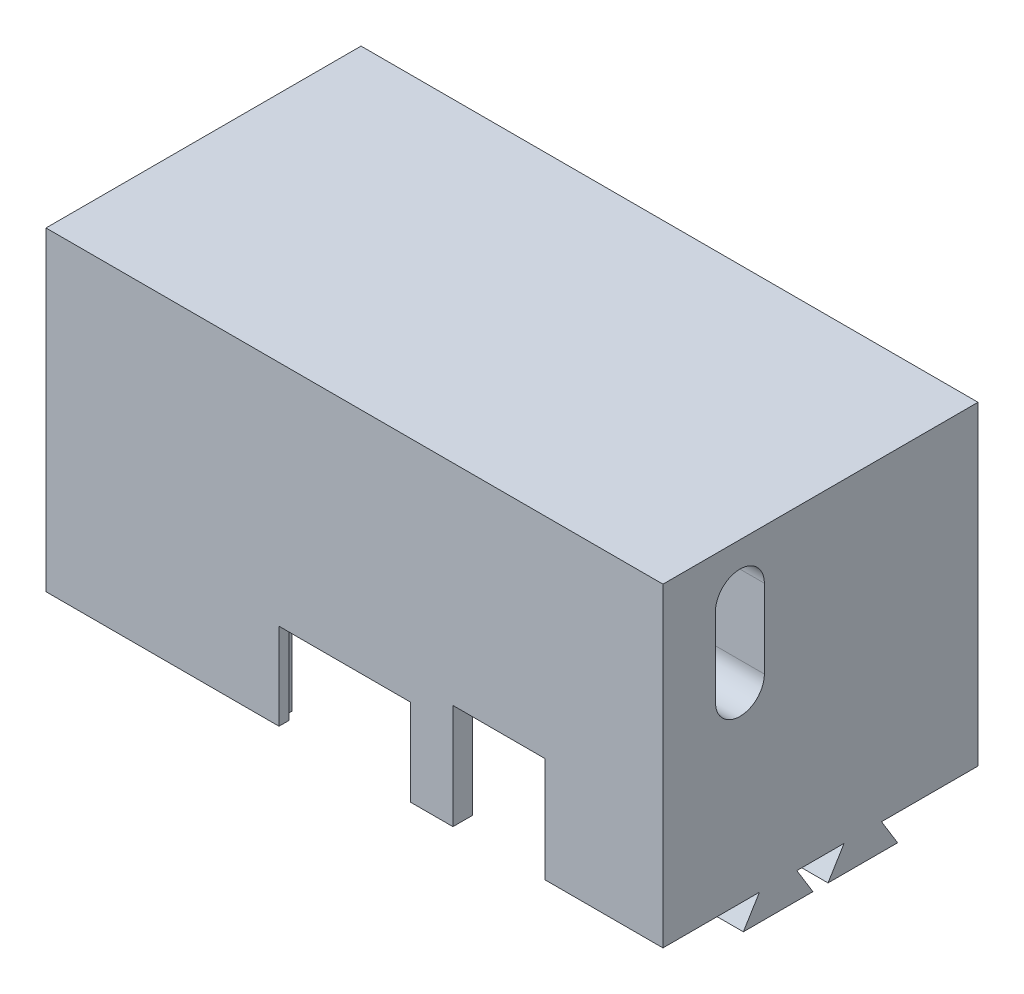
SolidWorks part; units mm, degrees
ref_plane "Front Plane" through (0, 0, 0) normal (0, 0, 1) x (1, 0, 0)
ref_plane "Top Plane" through (0, 0, 0) normal (0, 1, 0) x (1, 0, 0)
ref_plane "Right Plane" through (0, 0, 0) normal (1, 0, 0) x (0, 0, -1)
sketch "Sketch1" plane through (0, 0, 0) normal (0, 1, 0) x (1, 0, 0)
  line L0 (-47, -24) -> (47, 24) construction
  line L1 (-47, 24) -> (47, 24)
  line L2 (-47, 24) -> (-47, -24)
  line L3 (-47, -24) -> (47, -24)
  line L4 (47, 24) -> (47, -24)
  line L5 (-47, 24) -> (47, -24) construction
  point P4 (-47, 0)
  point P5 (0, 24)
  dimension "D1" = 48
  dimension "D2" = 94
extrude "Boss-Extrude1" add sketch "Sketch1" along normal blind 4
sketch "Sketch8" plane through (0, 0, 0) normal (0, -1, 0) x (-1, 0, 0)
  line L3 (47, -24) -> (-47, -24)
  line L4 (47, -24) -> (47, 24)
  line L5 (47, 24) -> (-47, 24)
  line L6 (-47, -24) -> (-47, 24)
  line L13 (47, -24) -> (-47, 24) construction
  line L14 (47, 24) -> (-47, -24) construction
  line L15 (34, -16) -> (-31, -16)
  line L16 (-31, -16) -> (-31, 6)
  line L17 (-31, 6) -> (-39, 6)
  line L18 (-39, 6) -> (-39, 19)
  line L19 (-39, 19) -> (-31, 19)
  line L20 (-31, 19) -> (-31, 16)
  line L21 (-31, 16) -> (34, 16)
  line L22 (34, 16) -> (34, -16)
  point P0 (47, 0)
  point P1 (0, -24)
  point P3 (0, 0)
  dimension "D1" = 48
  dimension "D2" = 94
  dimension "D3" = 65
  dimension "D4" = 32
  dimension "D5" = 13
  dimension "D6" = 3
  dimension "D7" = 8
  dimension "D8" = 8
  dimension "D9" = 8
  dimension "D10" = 8
extrude "Boss-Extrude2" add sketch "Sketch8" along normal blind 21
sketch "Sketch9" plane through (47, 0, 0) normal (1, 0, 0) x (0, 0, -1)
  line L0 (-12.2735, -3.6034) -> (-12.2735, -15.588) construction
  line L4 (-8.547, -3.6034) -> (-8.547, -15.588)
  line L5 (-16, -3.6034) -> (-16, -15.588)
  line L6 (-24, 4) -> (-24, -21) construction
  arc A2 (-8.547, -3.6034) -> (-16, -3.6034) centre (-12.2735, -3.6034) ccw
  arc A3 (-16, -15.588) -> (-8.547, -15.588) centre (-12.2735, -15.588) ccw
  point P2 (-12.2735, -9.5957)
  dimension "D1" = 8
extrude "Cut-Extrude1" cut sketch "Sketch9" against normal blind 16
sketch "Sketch10" plane through (0, -21, 0) normal (0, -1, 0) x (1, 0, 0)
  line L1 (-47, 24) -> (47, 24)
  line L2 (-47, 24) -> (-47, -24)
  line L3 (-47, -24) -> (47, -24)
  line L4 (47, 24) -> (47, -24)
  line L15 (31, -6) -> (39, -6)
  line L20 (-39, 21) -> (31, 21)
  line L21 (31, 21) -> (31, -6)
  line L22 (39, -6) -> (39, -19)
  line L23 (39, -19) -> (-39, -19)
  line L24 (-39, -19) -> (-39, 21)
  dimension "D1" = 40
  dimension "D2" = 70
  dimension "D3" = 8
  dimension "D4" = 3
  dimension "D5" = 8
  dimension "D6" = 13
extrude "Boss-Extrude3" add sketch "Sketch10" along normal blind 5
sketch "Sketch11" [suppressed] plane through (0, -21, 0) normal (0, -1, 0) x (-1, 0, 0)
  line L0 (-31, -17) -> (-31, -22) construction
  line L1 (39, -22) -> (-31, -22)
  line L2 (39, -22) -> (39, -19.5)
  line L3 (39, -19.5) -> (-31, -19.5)
  line L4 (-31, -22) -> (-31, -19.5)
  line L5 (-31, 15) -> (-31, 18) construction
  line L6 (-31, 15) -> (39, 15)
  line L7 (-31, 15) -> (-31, 18)
  line L8 (-31, 18) -> (39, 18)
  line L9 (39, 15) -> (39, 18)
  line L10 (34, 15) -> (-31, 15) construction
  line L11 (39, 18) -> (-31, 18) construction
  line L12 (39, -22) -> (39, 18) construction
sketch "Sketch15" plane through (0, -21, 0) normal (0, -1, 0) x (1, 0, 0)
  line L0 (31, 21) -> (31, -6) construction
  line L1 (-39, 21) -> (31, 21)
  line L2 (-39, 21) -> (-39, 19.5)
  line L3 (-39, 19.5) -> (31, 19.5)
  line L4 (31, 21) -> (31, 19.5)
  line L6 (31, -16) -> (-39, -16)
  line L7 (31, -16) -> (31, -19)
  line L8 (31, -19) -> (-39, -19)
  line L9 (-39, -16) -> (-39, -19)
  dimension "3" = 1.5
extrude "Boss-Extrude6" add sketch "Sketch15" along normal blind 4
sketch "Sketch16" plane through (0, -26, 0) normal (0, -1, 0) x (1, 0, 0)
  line L0 (-47, 24) -> (47, 24)
  line L1 (47, 24) -> (47, -24)
  line L2 (47, -24) -> (-47, -24)
  line L3 (-47, -24) -> (-47, 24)
  line L5 (-41, 21) -> (43, 21)
  line L6 (-41, 21) -> (-41, -22)
  line L7 (-41, -22) -> (43, -22)
  line L8 (43, 21) -> (43, -22)
  dimension "D1" = 2
  dimension "D2" = 4
  dimension "D3" = 3
  dimension "D4" = 6
extrude "Boss-Extrude7" add sketch "Sketch16" along normal blind 18
sketch "Sketch17" plane through (-47, 0, 0) normal (-1, 0, 0) x (0, 0, 1)
  line L0 (15, -37.2977) -> (15, -25.2486) construction
  line L1 (13.36, -37.2977) -> (13.36, -25.2486)
  line L2 (16.64, -37.2977) -> (16.64, -25.2486)
  line L3 (24, 4) -> (24, -44) construction
  line L4 (10.64, -37.2977) -> (10.64, -25.2486)
  line L5 (7.36, -37.2977) -> (7.36, -25.2486)
  line L6 (9, -37.2977) -> (9, -25.2486) construction
  line L7 (4.64, -37.2977) -> (4.64, -25.2486)
  line L8 (1.36, -37.2977) -> (1.36, -25.2486)
  line L9 (3, -37.2977) -> (3, -25.2486) construction
  line L10 (-1.36, -37.2977) -> (-1.36, -25.2486)
  line L11 (-4.64, -37.2977) -> (-4.64, -25.2486)
  line L12 (-3, -37.2977) -> (-3, -25.2486) construction
  line L13 (-7.36, -37.2977) -> (-7.36, -25.2486)
  line L14 (-10.64, -37.2977) -> (-10.64, -25.2486)
  line L15 (-9, -37.2977) -> (-9, -25.2486) construction
  line L16 (-13.36, -37.2977) -> (-13.36, -25.2486)
  line L17 (-16.64, -37.2977) -> (-16.64, -25.2486)
  line L18 (-15, -37.2977) -> (-15, -25.2486) construction
  line L20 (-24, 4) -> (-24, -44) construction
  arc A0 (13.36, -37.2977) -> (16.64, -37.2977) centre (15, -37.2977) ccw
  arc A1 (16.64, -25.2486) -> (13.36, -25.2486) centre (15, -25.2486) ccw
  arc A2 (7.36, -37.2977) -> (10.64, -37.2977) centre (9, -37.2977) ccw
  arc A3 (10.64, -25.2486) -> (7.36, -25.2486) centre (9, -25.2486) ccw
  arc A4 (1.36, -37.2977) -> (4.64, -37.2977) centre (3, -37.2977) ccw
  arc A5 (4.64, -25.2486) -> (1.36, -25.2486) centre (3, -25.2486) ccw
  arc A6 (-4.64, -37.2977) -> (-1.36, -37.2977) centre (-3, -37.2977) ccw
  arc A7 (-1.36, -25.2486) -> (-4.64, -25.2486) centre (-3, -25.2486) ccw
  arc A8 (-10.64, -37.2977) -> (-7.36, -37.2977) centre (-9, -37.2977) ccw
  arc A9 (-7.36, -25.2486) -> (-10.64, -25.2486) centre (-9, -25.2486) ccw
  arc A10 (-16.64, -37.2977) -> (-13.36, -37.2977) centre (-15, -37.2977) ccw
  arc A11 (-13.36, -25.2486) -> (-16.64, -25.2486) centre (-15, -25.2486) ccw
  point P2 (15, -31.2732)
  point P12 (9, -31.2732)
  point P20 (3, -31.2732)
  point P27 (-3, -31.2732)
  point P34 (-9, -31.2732)
  point P41 (-15, -31.2732)
  dimension "D1" = 9
  dimension "D2" = 6
  dimension "D3" = 9
extrude "Cut-Extrude4" cut sketch "Sketch17" against normal blind 8
sketch "Sketch18" plane through (0, -44, 0) normal (0, -1, 0) x (1, 0, 0)
  line L0 (-47, 24) -> (-47, -24) construction
  line L1 (-47, 10) -> (-45, 10)
  line L2 (-47, 10) -> (-47, -10)
  line L3 (-47, -10) -> (-45, -10)
  line L4 (-45, 10) -> (-45, -10)
  dimension "D1" = 20
  dimension "D2" = 2
  dimension "D3" = 14
extrude "Boss-Extrude8" add sketch "Sketch18" along normal blind 6
sketch "Sketch19" plane through (-45, 0, 0) normal (1, 0, 0) x (0, 0, -1)
  line L0 (0, -50) -> (0, -44) construction
  line L1 (10, -50) -> (-10, -50) construction
  line L2 (10, -44) -> (-10, -44) construction
  line L3 (-5.55, -44) -> (5.55, -44)
  line L4 (5.55, -44) -> (7.8, -48)
  line L5 (7.8, -48) -> (-7.8, -48)
  line L6 (-5.55, -44) -> (-7.8, -48)
  point P10 (0, -48)
  dimension "D1" = 5.55
  dimension "D2" = 7.8
  dimension "D3" = 4
extrude "Boss-Extrude9" add sketch "Sketch19" along normal blind 4
ref_plane "Plane1" through (47, 0, 0) normal (1, 0, 0) x (0, 0, -1)
sketch "Sketch20" plane through (47, 0, 0) normal (1, 0, 0) x (0, 0, -1)
  line L0 (0, 6.423) -> (0, -57.999) construction
  line L1 (6.45, 4) -> (6.45, -54.5279) construction
  line L2 (-24, 4) -> (24, 4) construction
  line L3 (3.6, -44) -> (9.3, -44)
  line L4 (24, -44) -> (-24, -44) construction
  line L5 (9.3, -44) -> (11.75, -48)
  line L6 (11.75, -48) -> (1.15, -48)
  line L7 (3.6, -44) -> (1.15, -48)
  line L8 (-3.6, -44) -> (-1.15, -48)
  line L9 (-11.75, -48) -> (-1.15, -48)
  line L10 (-9.3, -44) -> (-11.75, -48)
  line L11 (-3.6, -44) -> (-9.3, -44)
  point P15 (6.45, -48)
  point P16 (6.45, -44)
  point P21 (-6.45, -44)
  point P22 (-6.45, -48)
  dimension "D1" = 5.3
  dimension "D2" = 4
  dimension "D3" = 2.85
  dimension "D4" = 12.25
  dimension "D5" = 12.25
  dimension "D6" = 3.6
extrude "Boss-Extrude10" add sketch "Sketch20" against normal blind 4
sketch "Sketch22" plane through (0, 0, 24) normal (0, 0, 1) x (1, 0, 0)
  line L0 (47, -44) -> (-47, -44) construction
  line L1 (29, -44) -> (15, -44)
  line L2 (29, -44) -> (29, -28)
  line L3 (29, -28) -> (15, -28)
  line L4 (15, -44) -> (15, -28)
  line L5 (47, -26.4) -> (47, 26.4) construction
  dimension "D1" = 14
  dimension "D2" = 16
  dimension "D3" = 18
extrude "Cut-Extrude6" cut sketch "Sketch22" against normal blind 3
extrude "Boss-Extrude4" [suppressed] add sketch "Sketch11" along normal blind 4
sketch "Sketch28" plane through (0, -44, 0) normal (0, -1, 0) x (-1, 0, 0)
  line L0 (-8.5, -24) -> (-8.5, -22.5)
  line L1 (47, -24) -> (-47, -24) construction
  line L2 (-8.5, -22.5) -> (-9.5, -22.5)
  line L3 (-9.5, -22.5) -> (-9.5, -21)
  line L4 (39, -21) -> (-31, -21) construction
  line L5 (-9.5, -21) -> (12.5, -21)
  line L6 (12.5, -21) -> (12.5, -22.5)
  line L7 (12.5, -22.5) -> (11.5, -22.5)
  line L8 (11.5, -22.5) -> (11.5, -24)
  line L9 (11.5, -24) -> (-8.5, -24)
  dimension "D1" = 20
  dimension "D2" = 22
  dimension "D3" = 1.5
  dimension "D4" = 1.5
  dimension "D5" = 1
  dimension "D6" = 1
  dimension "D7" = 6.5
extrude "Cut-Extrude8" cut sketch "Sketch28" against normal blind 13.2
